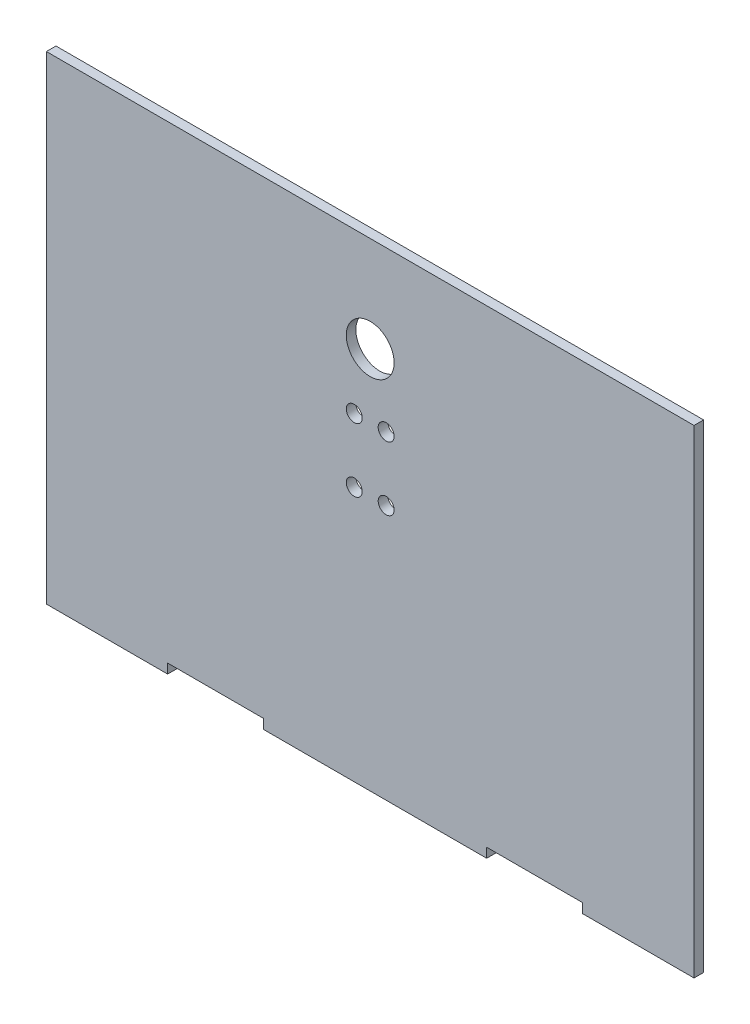
SolidWorks part; units mm, degrees
ref_plane "Front Plane" through (0, 0, 0) normal (0, 0, 1) x (1, 0, 0)
ref_plane "Top Plane" through (0, 0, 0) normal (0, 1, 0) x (1, 0, 0)
ref_plane "Right Plane" through (0, 0, 0) normal (1, 0, 0) x (0, 0, -1)
sketch "Sketch1" plane through (0, 0, 0) normal (0, 0, 1) x (1, 0, 0)
  line L1 (-101.5, 75) -> (101.5, 75)
  line L2 (-101.5, 75) -> (-101.5, -75)
  line L3 (-101.5, -75) -> (101.5, -75)
  line L4 (101.5, 75) -> (101.5, -75)
  line L5 (-101.5, 75) -> (101.5, -75) construction
  line L6 (-101.5, -75) -> (101.5, 75) construction
  point P0 (0, 0)
  dimension "D1" = 150
  dimension "D2" = 203
extrude "Boss-Extrude1" add sketch "Sketch1" along normal blind 3
sketch "Sketch3" plane through (0, 0, 3) normal (0, 0, 1) x (1, 0, 0)
  line L0 (0, -75) -> (0, 75) construction
  line L1 (-101.5, -75) -> (101.5, -75) construction
  line L2 (101.5, 75) -> (-101.5, 75) construction
  circle A0 centre (0, 45) radius 7.5
  circle A1 centre (-5, 25) radius 2.5
  circle A2 centre (-5, 5) radius 2.5
  circle A3 centre (5, 5) radius 2.5
  circle A4 centre (5, 25) radius 2.5
  dimension "D1" = 15
  dimension "D3" = 5
  dimension "D4" = 5
  dimension "D2" = 30
  dimension "D5" = 5
  dimension "D6" = 20
  dimension "D7" = 20
extrude "Cut-Extrude2" cut sketch "Sketch3" against normal blind 10
sketch "Sketch4" plane through (0, 0, 3) normal (0, 0, 1) x (1, 0, 0)
  line L0 (-101.5, -75) -> (101.5, -75) construction
  line L1 (-63.5, -75) -> (-33.5, -75)
  line L2 (-63.5, -75) -> (-63.5, -72)
  line L3 (-63.5, -72) -> (-33.5, -72)
  line L4 (-33.5, -75) -> (-33.5, -72)
  line L5 (-48.5, -75) -> (-48.5, -72) construction
  line L6 (-101.5, 75) -> (-101.5, -75) construction
  line L7 (36.5, -75) -> (36.5, -72)
  line L8 (36.5, -75) -> (66.5, -75)
  line L9 (66.5, -75) -> (66.5, -72)
  line L10 (36.5, -72) -> (66.5, -72)
  dimension "D1" = 30
  dimension "D2" = 3
  dimension "D3" = 53
  dimension "D4" = 2
extrude "Cut-Extrude3" cut sketch "Sketch4" against normal blind 10
